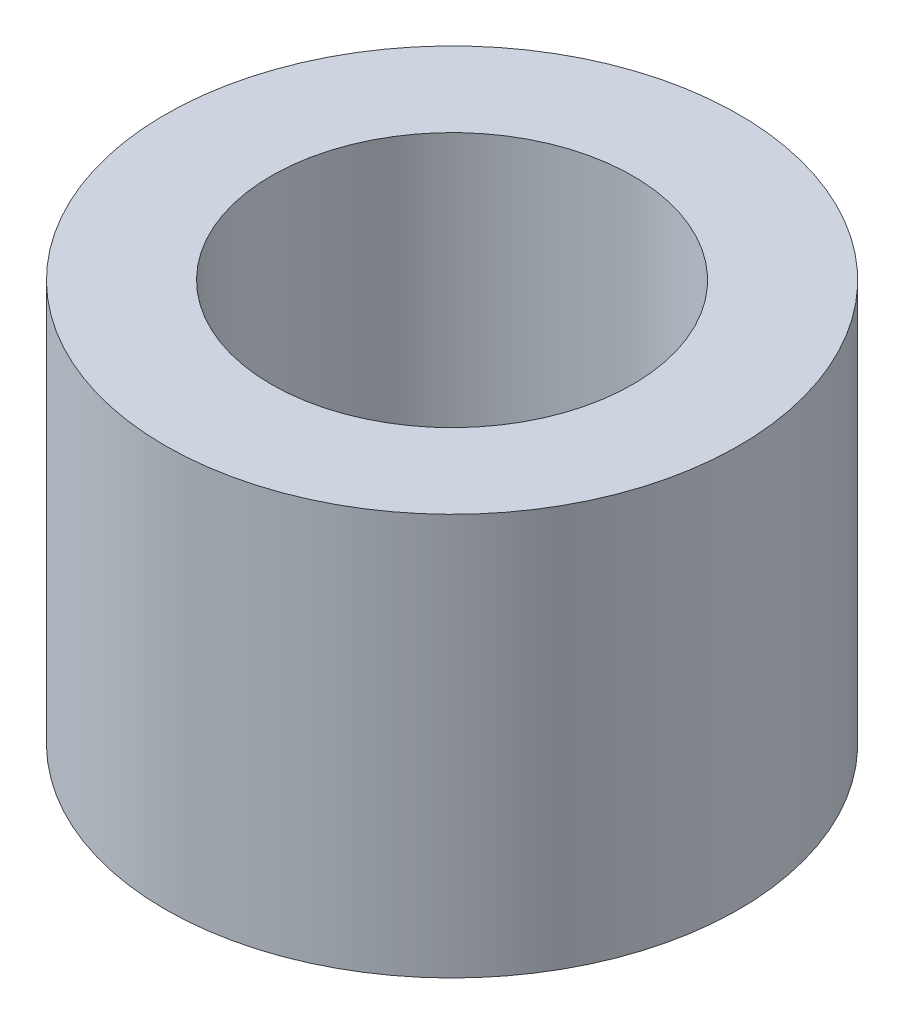
SolidWorks part; units mm, degrees
material "ABS"
ref_plane "前视基准面" through (0, 0, 0) normal (0, 0, 1) x (1, 0, 0)
ref_plane "上视基准面" through (0, 0, 0) normal (0, 1, 0) x (1, 0, 0)
ref_plane "右视基准面" through (0, 0, 0) normal (1, 0, 0) x (0, 0, -1)
other "Configuration Table"
sketch "草图1" plane through (0, 0, 0) normal (0, 1, 0) x (1, 0, 0)
  circle A0 centre (0, 0) radius 3.15
  circle A1 centre (0, 0) radius 5
  dimension "D1" = 6.3
  dimension "D2" = 10
extrude "凸台-拉伸1" add sketch "草图1" along normal blind 7
